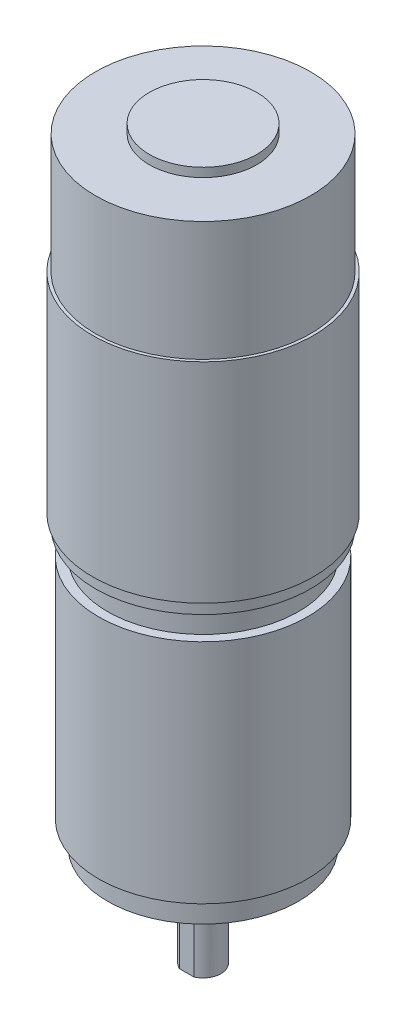
SolidWorks part; units mm, degrees
ref_plane "Спереди" through (0, 0, 0) normal (0, 0, 1) x (1, 0, 0)
ref_plane "Сверху" through (0, 0, 0) normal (0, 1, 0) x (1, 0, 0)
ref_plane "Справа" through (0, 0, 0) normal (1, 0, 0) x (0, 0, -1)
sketch "Эскиз1" plane through (0, 0, 0) normal (0, 0, 1) x (1, 0, 0)
  line L0 (0, -180.9093) -> (0, 224.9568) construction
  line L1 (0, 0) -> (-9, 0)
  line L2 (-9, 0) -> (-9, -1.5)
  line L3 (-9, -1.5) -> (-18, -1.5)
  line L4 (-18, -1.5) -> (-18, -21.5)
  line L5 (-18, -21.5) -> (-18.5, -21.5)
  line L6 (-18.5, -21.5) -> (-18.5, -56.5)
  line L7 (-18.5, -56.5) -> (-18, -56.5)
  line L8 (-18, -56.5) -> (-18, -58.5)
  line L9 (-18, -58.5) -> (-16, -58.5)
  line L10 (-16, -58.5) -> (-16, -62.8)
  line L11 (-16, -62.8) -> (-17.5, -62.8)
  line L12 (-17.5, -62.8) -> (-17.5, -100.8)
  line L13 (-17.5, -100.8) -> (-16, -100.8)
  line L14 (-16, -100.8) -> (-16, -104.8)
  line L15 (-16, -104.8) -> (-10, -104.8)
  line L16 (-10, -104.8) -> (-10, -106.8)
  line L17 (-10, -106.8) -> (-3, -106.8)
  line L20 (-3, -106.8) -> (-3, -121.8)
  line L21 (-3, -121.8) -> (0, -121.8)
  line L22 (0, 0) -> (0, -121.8)
  point P23 (0, 0)
  point P24 (0, 0)
  point P26 (0, 0)
  point P27 (0, 0)
  point P28 (0, 0)
  dimension "D3" = 10
  dimension "D4" = 16
  dimension "D6" = 15
  dimension "D7" = 17.5
  dimension "D8" = 16
  dimension "D9" = 18
  dimension "D10" = 18
  dimension "D11" = 18.5
  dimension "D12" = 20
  dimension "D13" = 2
  dimension "D14" = 4
  dimension "D15" = 38
  dimension "D17" = 2
  dimension "D18" = 35
  dimension "D19" = 9
  dimension "D20" = 1.5
  dimension "D21" = 4.3
  dimension "D22" = 1.5
  dimension "D23" = 3
revolve "Повернуть1" add sketch "Эскиз1" angle 360 about L0
sketch "Эскиз4" plane through (0, -121.8, 0) normal (0, -1, 0) x (1, 0, 0)
  line L1 (-3, 2.75) -> (3, 2.75)
  line L2 (-3, 2.75) -> (-3, -2.75)
  line L3 (-3, -2.75) -> (3, -2.75)
  line L4 (3, 2.75) -> (3, -2.75)
  line L5 (-3, 2.75) -> (3, -2.75) construction
  line L6 (-3, -2.75) -> (3, 2.75) construction
  circle A0 centre (0, 0) radius 3 construction
  circle A1 centre (0, 0) radius 3 construction
  point P0 (0, 0)
  dimension "D1" = 2.75
extrude "Вырез-Вытянуть2" cut sketch "Эскиз4" against normal blind 12 flip side to cut
sketch "Эскиз5" plane through (0, -104.8, 0) normal (0, -1, 0) x (1, 0, 0)
  line L4 (-9, 9) -> (9, 9) construction
  line L5 (-9, 9) -> (-9, -9) construction
  line L6 (-9, -9) -> (9, -9) construction
  line L7 (9, 9) -> (9, -9) construction
  line L8 (-9, 9) -> (9, -9) construction
  line L9 (-9, -9) -> (9, 9) construction
  circle A0 centre (-9, 9) radius 1.5
  circle A1 centre (9, 9) radius 1.5
  circle A2 centre (9, -9) radius 1.5
  circle A3 centre (-9, -9) radius 1.5
  point P8 (0, 0)
  point P9 (0, 0)
  point P10 (-13.0272, 9)
  point P12 (8.4695, -13.3376)
  point P13 (0, 0)
  point P14 (0, 0)
  point P15 (-9, -9)
  point P16 (0, 0)
  point P18 (0, 0)
  point P19 (0, 0)
  point P20 (0, 0)
  point P21 (0, 0)
  dimension "D1" = 3
  dimension "D2" = 3
  dimension "D3" = 3
  dimension "D4" = 3
  dimension "D6" = 18
  dimension "D9" = 18
extrude "Вырез-Вытянуть3" cut sketch "Эскиз5" against normal blind 5
